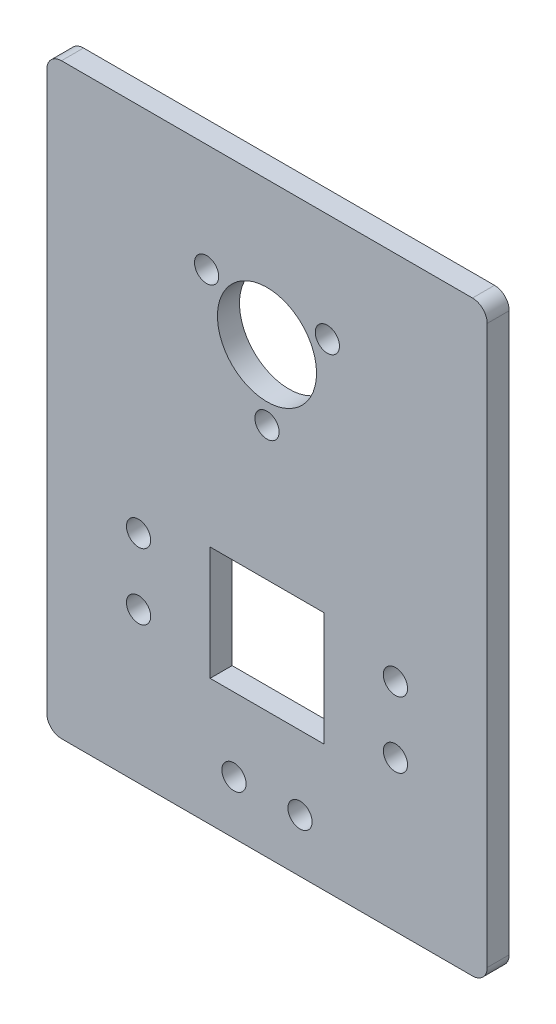
SolidWorks part; units mm, degrees
ref_plane "前视基准面" through (0, 0, 0) normal (0, 0, 1) x (1, 0, 0)
ref_plane "上视基准面" through (0, 0, 0) normal (0, 1, 0) x (1, 0, 0)
ref_plane "右视基准面" through (0, 0, 0) normal (1, 0, 0) x (0, 0, -1)
sketch "草图1" plane through (0, 0, 0) normal (0, 0, 1) x (1, 0, 0)
  line L1 (-30, -45) -> (30, -45)
  line L2 (-30, -45) -> (-30, 45)
  line L3 (-30, 45) -> (30, 45)
  line L4 (30, -45) -> (30, 45)
  line L5 (-30, -45) -> (30, 45) construction
  line L6 (-30, 45) -> (30, -45) construction
  point P0 (0, 0)
  dimension "D1" = 90
  dimension "D2" = 60
extrude "凸台-拉伸1" add sketch "草图1" along normal blind 3
sketch "草图2" plane through (0, 0, 3) normal (0, 0, 1) x (1, 0, 0)
  line L0 (0, 64.4871) -> (0, -56.8412) construction
  line L1 (-30, -45) -> (30, -45) construction
  circle A0 centre (0, 25.5) radius 9.5 construction
  circle A1 centre (0, 16) radius 1.65
  circle A2 centre (-8.2272, 30.25) radius 1.65
  circle A3 centre (8.2272, 30.25) radius 1.65
  dimension "D1" = 70.5
  dimension "D2" = 19
  dimension "D3" = 3.3
  dimension "D4" = 3
extrude "切除-拉伸1" cut sketch "草图2" against normal blind 3
sketch "草图5" plane through (0, 0, 3) normal (0, 0, 1) x (1, 0, 0)
  line L0 (0, 64.4871) -> (0, -56.8412) construction
  line L1 (-7.75, -2.25) -> (7.75, -2.25)
  line L2 (-7.75, -2.25) -> (-7.75, -17.75)
  line L3 (-7.75, -17.75) -> (7.75, -17.75)
  line L4 (7.75, -2.25) -> (7.75, -17.75)
  line L5 (-7.75, -2.25) -> (7.75, -17.75) construction
  line L6 (-7.75, -17.75) -> (7.75, -2.25) construction
  line L8 (-30, -45) -> (30, -45) construction
  point P0 (0, -10)
  dimension "D1" = 15.5
  dimension "D2" = 15.5
  dimension "D3" = 35
extrude "切除-拉伸4" cut sketch "草图5" against normal blind 1000
sketch "草图3" plane through (0, 0, 3) normal (0, 0, 1) x (1, 0, 0)
  line L0 (0, 19.1236) -> (0, -38.6111) construction
  line L1 (-4.5, -27.75) -> (4.5, -27.75) construction
  line L3 (-7.75, -17.75) -> (7.75, -17.75) construction
  circle A0 centre (4.5, -27.75) radius 1.65
  circle A1 centre (-4.5, -27.75) radius 1.65
  dimension "D1" = 3.3
  dimension "D2" = 3.3
  dimension "D4" = 4.5
  dimension "D5" = 4.5
  dimension "D3" = 10
extrude "切除-拉伸2" cut sketch "草图3" against normal blind 3
sketch "草图4" plane through (0, 0, 3) normal (0, 0, 1) x (1, 0, 0)
  circle A0 centre (0, 25.5) radius 6.75
  dimension "D1" = 13.5
extrude "切除-拉伸3" cut sketch "草图4" against normal blind 3
fillet "圆角1" radius 2 2 edges at (30, 45, 1.5) (-30, 45, 1.5)
sketch "草图6" plane through (0, 0, 3) normal (0, 0, 1) x (1, 0, 0)
  line L0 (0, 64.4871) -> (0, -56.8412) construction
  line L1 (-34.5555, -47.8629) -> (34.5555, -47.8629)
  line L2 (-34.5555, -47.8629) -> (-34.5555, -35)
  line L3 (-34.5555, -35) -> (34.5555, -35)
  line L4 (34.5555, -47.8629) -> (34.5555, -35)
  line L5 (-34.5555, -47.8629) -> (34.5555, -35) construction
  line L6 (-34.5555, -35) -> (34.5555, -47.8629) construction
  line L7 (-30, -45) -> (30, -45) construction
  point P0 (0, -41.4315)
  dimension "D1" = 10
extrude "切除-拉伸5" cut sketch "草图6" against normal blind 1000
fillet "圆角2" radius 2 2 edges at (30, -35, 1.5) (-30, -35, 1.5)
sketch "草图7" plane through (0, 0, 3) normal (0, 0, 1) x (1, 0, 0)
  line L0 (-7.75, -10) -> (62.2436, -10) construction
  line L1 (-7.75, -2.25) -> (-7.75, -17.75) construction
  line L2 (17.5, 4.5315) -> (17.5, -28.934) construction
  line L3 (-17.5, 7.3657) -> (-17.5, -25.6637) construction
  line L4 (0, 64.4871) -> (0, -56.8412) construction
  circle A0 centre (17.5, -5.5) radius 1.65
  circle A1 centre (17.5, -14.5) radius 1.65
  circle A2 centre (-17.5, -5.5) radius 1.65
  circle A3 centre (-17.5, -14.5) radius 1.65
  dimension "D7" = 3.3
  dimension "D8" = 3.3
  dimension "D9" = 3.3
  dimension "D10" = 3.3
  dimension "D1" = 17.5
  dimension "D2" = 17.5
  dimension "D3" = 4.5
  dimension "D4" = 4.5
  dimension "D5" = 4.5
  dimension "D6" = 4.5
extrude "切除-拉伸6" cut sketch "草图7" against normal blind 1000
